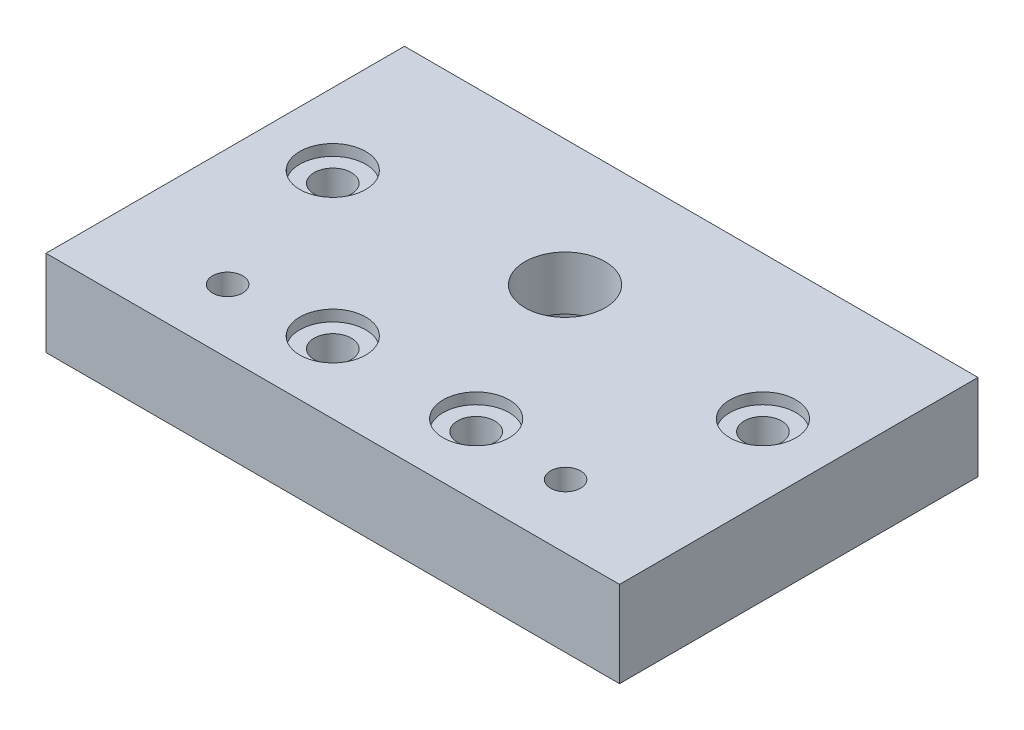
SolidWorks part; units mm, degrees
material "6061-T6 (SS)"
ref_plane "Front Plane" through (0, 0, 0) normal (0, 0, 1) x (1, 0, 0)
ref_plane "Top Plane" through (0, 0, 0) normal (0, 1, 0) x (1, 0, 0)
ref_plane "Right Plane" through (0, 0, 0) normal (1, 0, 0) x (0, 0, -1)
sketch "Sketch1" plane through (0, 0, 0) normal (0, 1, 0) x (1, 0, 0)
  line L5 (-40, 25) -> (40, 25)
  line L6 (-40, 25) -> (-40, -25)
  line L7 (-40, -25) -> (40, -25)
  line L8 (40, 25) -> (40, -25)
  line L9 (-40, 25) -> (40, -25) construction
  line L10 (-40, -25) -> (40, 25) construction
  point P0 (0, 0)
  dimension "D1" = 50
  dimension "D2" = 80
extrude "Boss-Extrude1" add sketch "Sketch1" along normal blind 12
sketch "Sketch5" plane through (0, 12, 0) normal (0, 1, 0) x (1, 0, 0)
  line L0 (-30, 25) -> (-30, -25) construction
  line L1 (40, 25) -> (-40, 25) construction
  line L2 (-40, -25) -> (40, -25) construction
  line L3 (-40, 5) -> (-30, 5) construction
  line L4 (-40, 25) -> (-40, -25) construction
  line L5 (40, -25) -> (40, 25) construction
  line L6 (-40, -15) -> (40, -15) construction
  line L7 (-10, -25) -> (-10, -15) construction
  line L8 (-23.57, -25) -> (-23.57, -16.1) construction
  line L9 (-40, -16.1) -> (-23.57, -16.1) construction
  line L10 (-10, -16.1) -> (40, -16.1) construction
  dimension "D1" = 10
  dimension "D2" = 30
  dimension "D3" = 10
  dimension "D4" = 30
  dimension "D5" = 8.9
  dimension "D6" = 16.43
hole_wizard "Hole2" positions "Sketch8" profile "Sketch9" legacy
sketch "Sketch8" plane through (0, 12, 0) normal (0, 1, 0) x (1, 0, 0)
  point P0 (-30, 5)
  point P3 (-10, -15)
sketch "Sketch9" plane through (-30, 12, -5) normal (1, 0, 0) x (0, 0, 1)
  line L0 (0, 0) -> (0, 13.5622)
  line L1 (0, 13.5622) -> (2.6, 12)
  line L2 (2.6, 12) -> (2.6, 1.55)
  line L3 (2.6, 1.55) -> (4.6, 1.55)
  line L4 (4.6, 0) -> (0, 0)
  line L5 (0, -11.3109) -> (0, 121.1557) construction
  line L6 (0, 13.5622) -> (-2.6, 12) construction
  line L7 (4.6, 1.55) -> (4.6, 0)
  dimension "Depth" = 12
  dimension "Drill Angle" = 118
  dimension "Diameter" = 5.2
  dimension "C-Bore Diameter" = 9.2
  dimension "C-Bore Depth" = 1.55
mirror "Mirror1" about plane through (0, 0, 0) normal (1, 0, 0) of "Hole2"
hole_wizard "Ø4.2 (4.2) Diameter Hole1" positions "Sketch10" profile "Sketch11" hole size "Ø4.2" standard "ANSI Metric"
sketch "Sketch10" plane through (0, 12, 0) normal (0, 1, 0) x (1, 0, 0)
  point P0 (-23.57, -16.1)
sketch "Sketch11" plane through (-23.57, 12, 16.1) normal (1, 0, 0) x (0, 0, 1)
  line L0 (0, 0) -> (0, 13.2618)
  line L1 (0, 13.2618) -> (2.1, 12)
  line L2 (2.1, 12) -> (2.1, 0)
  line L5 (2.1, 0) -> (0, 0)
  line L10 (0, 13.2618) -> (-2.1, 12) construction
  line L11 (0, -6.35) -> (0, 107.95) construction
  dimension "Hole Dia." = 4.2
  dimension "Hole Depth" = 12
  dimension "Drill Angle" = 118
mirror "Mirror2" about plane through (0, 0, 0) normal (1, 0, 0) of "Ø4.2 (4.2) Diameter Hole1"
sketch "Sketch12" plane through (0, 0, 0) normal (0, -1, 0) x (1, 0, 0)
  line L0 (0, -7.4) -> (0, -25) construction
  line L1 (40, -25) -> (-40, -25) construction
  line L2 (-40, -7.4) -> (40, -7.4) construction
  line L3 (-40, -25) -> (-40, 25) construction
  line L4 (40, 25) -> (40, -25) construction
  line L5 (-40, 25) -> (40, 25) construction
  dimension "D1" = 32.4
hole_wizard "CBORE for M10 Hex Head Bolt2" positions "Sketch17" profile "Sketch18" counterbore size "M10" standard "ANSI Metric" end condition through all
sketch "Sketch17" plane through (0, 0, 0) normal (0, -1, 0) x (-1, 0, 0)
  point P0 (0, 7.4)
sketch "Sketch18" plane through (0, 0, -7.4) normal (1, 0, 0) x (0, 0, -1)
  line L0 (0, 0) -> (0, 12)
  line L1 (0, 12) -> (5.588, 12)
  line L3 (5.588, 12) -> (5.588, 4.5)
  line L4 (5.588, 4.5) -> (8.05, 4.5)
  line L5 (8.05, 4.5) -> (8.05, 0)
  line L7 (8.05, 0) -> (0, 0)
  line L11 (0, -6.35) -> (0, 107.95) construction
  dimension "Thru Hole Dia." = 11.176
  dimension "Thru Hole Depth" = 12
  dimension "C'Bore Dia." = 16.1
  dimension "C'Bore Depth" = 4.5
sketch "Sketch19" plane through (0, 0, -25) normal (0, 0, -1) x (-1, 0, 0)
  line L0 (-10, 12) -> (-10, 0) construction
  line L1 (10, 12) -> (-40, 12) construction
  line L2 (40, 0) -> (-40, 0) construction
  line L3 (-40, 6) -> (-10, 6) construction
  line L4 (-40, 12) -> (-40, 0) construction
  dimension "D1" = 30
hole_wizard "Ø4.2 (4.2) Diameter Hole2" positions "Sketch20" profile "Sketch21" hole size "Ø4.2" standard "ANSI Metric"
sketch "Sketch20" plane through (0, 0, -25) normal (0, 0, -1) x (-1, 0, 0)
  line L0 (-10, 12) -> (-10, 0) construction
  point P0 (-10, 6)
sketch "Sketch21" plane through (10, 6, -25) normal (1, 0, 0) x (0, 1, 0)
  line L0 (0, 0) -> (0, 15.2618)
  line L1 (0, 15.2618) -> (2.1, 14)
  line L2 (2.1, 14) -> (2.1, 0)
  line L5 (2.1, 0) -> (0, 0)
  line L10 (0, 15.2618) -> (-2.1, 14) construction
  line L11 (0, -6.35) -> (0, 107.95) construction
  dimension "Hole Dia." = 4.2
  dimension "Hole Depth" = 14
  dimension "Drill Angle" = 118
mirror "Mirror3" about plane through (0, 0, 0) normal (1, 0, 0) of "Ø4.2 (4.2) Diameter Hole2"
